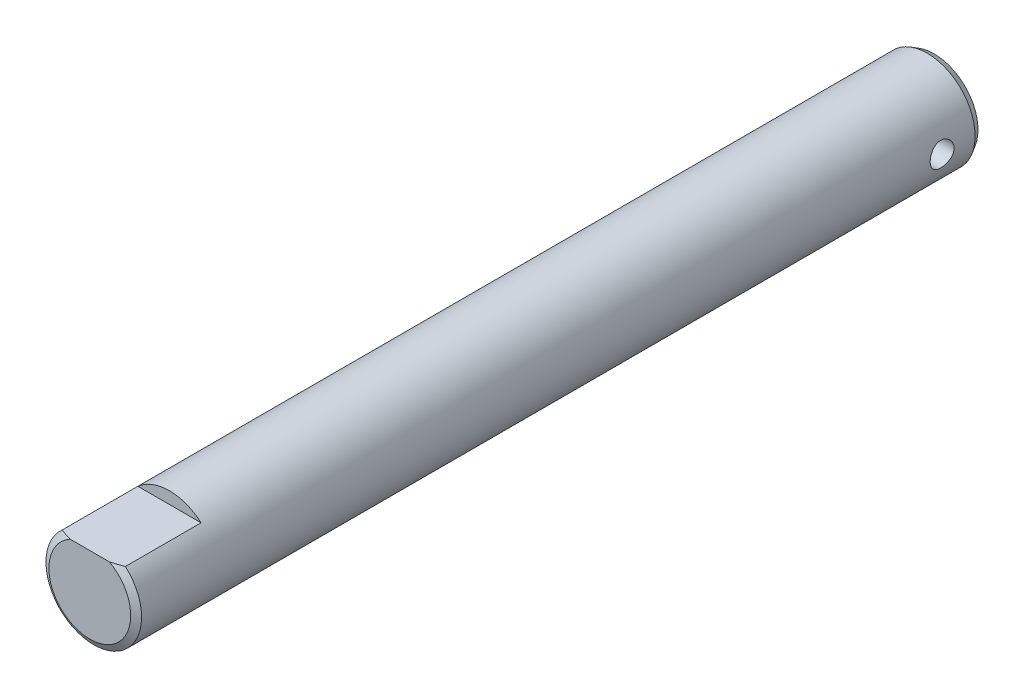
SolidWorks part; units mm, degrees
ref_plane "Front Plane" through (0, 0, 0) normal (0, 0, 1) x (1, 0, 0)
ref_plane "Top Plane" through (0, 0, 0) normal (0, 1, 0) x (1, 0, 0)
ref_plane "Right Plane" through (0, 0, 0) normal (1, 0, 0) x (0, 0, -1)
sketch "Sketch1" plane through (0, 0, 0) normal (0, 0, 1) x (1, 0, 0)
  circle A0 centre (0, 0) radius 6
  dimension "D1" = 12
extrude "Boss-Extrude1" add sketch "Sketch1" along normal blind 106
sketch "Sketch2" plane through (0, 0, 106) normal (0, 0, 1) x (1, 0, 0)
  line L1 (-6.4487, 8.1063) -> (6.9304, 8.1063)
  line L2 (-6.4487, 8.1063) -> (-6.4487, 4.5)
  line L3 (-6.4487, 4.5) -> (6.9304, 4.5)
  line L4 (6.9304, 8.1063) -> (6.9304, 4.5)
  dimension "D1" = 4.5
extrude "Cut-Extrude1" cut sketch "Sketch2" against normal blind 10
sketch "Sketch3" plane through (0, 0, 0) normal (1, 0, 0) x (0, 0, -1)
  circle A0 centre (-5, 0) radius 1.5
  dimension "D1" = 3
  dimension "D2" = 5
extrude "Cut-Extrude2" cut sketch "Sketch3" against normal through all and the other way through all
chamfer "Chamfer1" distance 0.5 angle 60 2 edges at (0, -6, 106) (6, 0, 0)
